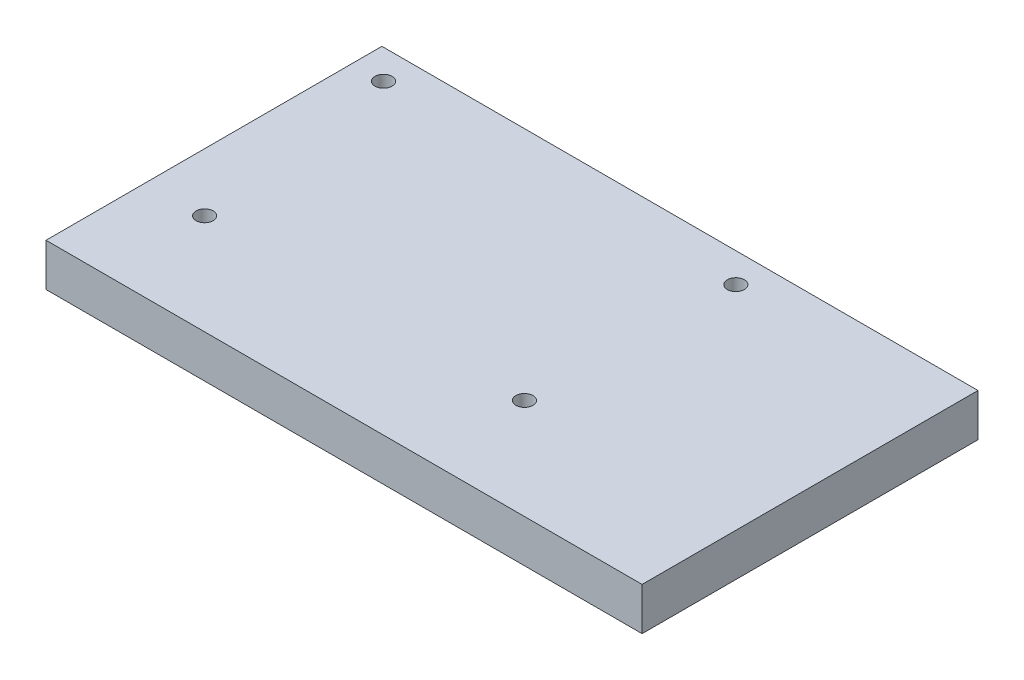
SolidWorks part; units mm, degrees
ref_plane "Front Plane" through (0, 0, 0) normal (0, 0, 1) x (1, 0, 0)
ref_plane "Top Plane" through (0, 0, 0) normal (0, 1, 0) x (1, 0, 0)
ref_plane "Right Plane" through (0, 0, 0) normal (1, 0, 0) x (0, 0, -1)
sketch "Sketch1" plane through (0, 0, 0) normal (0, 1, 0) x (1, 0, 0)
  line L1 (0, 0) -> (139.6686, 0)
  line L2 (0, 0) -> (0, -78.7062)
  line L3 (0, -78.7062) -> (139.6686, -78.7062)
  line L4 (139.6686, 0) -> (139.6686, -78.7062)
  point P4 (139.6686, -78.7062)
sketch "Sketch2" plane through (0, 0, 0) normal (0, 1, 0) x (1, 0, 0)
  line L0 (89.8265, -6.9012) -> (7.2765, -6.9012) construction
  circle A6 centre (88.5565, -55.1612) radius 2
  circle A7 centre (89.8265, -6.9012) radius 2
  circle A8 centre (37.7565, -11.9812) radius 2 construction
  circle A9 centre (37.7565, -39.9212) radius 2 construction
  circle A10 centre (13.6265, -55.1612) radius 2
  circle A11 centre (7.2765, -6.9012) radius 2
  point P0 (89.8265, -6.9012)
  point P1 (37.7565, -11.9812)
  point P2 (37.7565, -39.9212)
  point P3 (13.6265, -55.1612)
  point P4 (7.2765, -6.9012)
  point P5 (88.5565, -55.1612)
  point P18 (0, 0)
  point P19 (0, 0)
  point P20 (0, 0)
  point P21 (0, 0)
  point P22 (0, 0)
  point P24 (0, 0)
  point P25 (0, 0)
  point P26 (10.7283, -15.668)
  point P27 (7.2765, -6.9012)
  dimension "D5" = 4
  dimension "D1" = 48.26
  dimension "D2" = 30.48
  dimension "D3" = 5.08
  dimension "D4" = 27.94
  dimension "D6" = 82.55
  dimension "D7" = 6.35
  dimension "D8" = 81.28
extrude "Boss-Extrude1" add sketch "Sketch1" along normal blind 10
extrude "Cut-Extrude1" cut sketch "Sketch2" along normal through all
